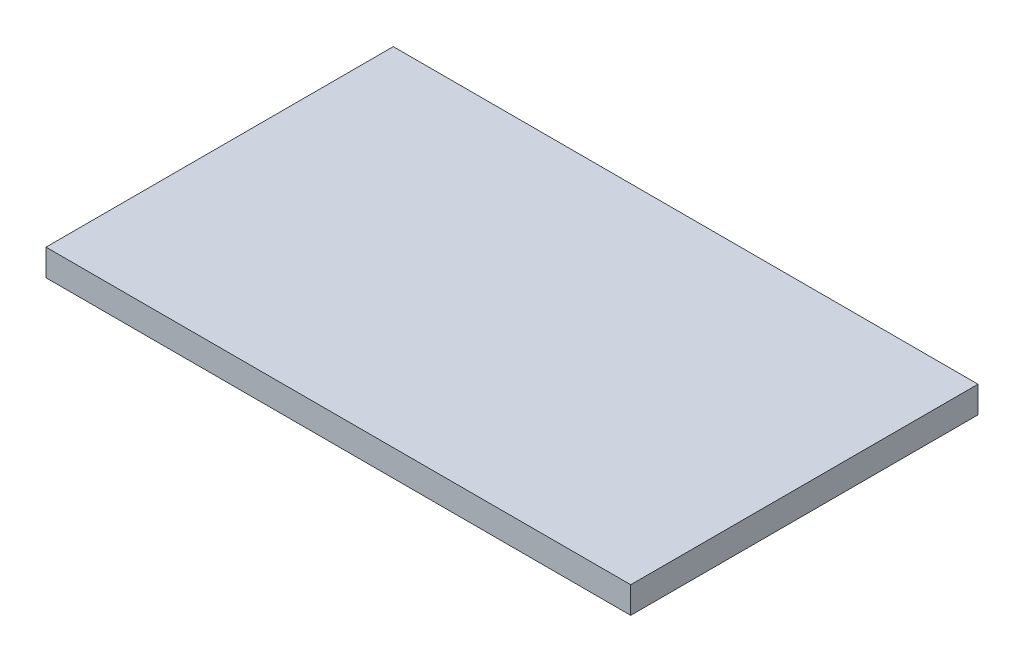
SolidWorks part; units mm, degrees
ref_plane "Front Plane" through (0, 0, 0) normal (0, 0, 1) x (1, 0, 0)
ref_plane "Top Plane" through (0, 0, 0) normal (0, 1, 0) x (1, 0, 0)
ref_plane "Right Plane" through (0, 0, 0) normal (1, 0, 0) x (0, 0, -1)
other "Configuration Table"
sketch "Sketch1" plane through (0, 0, 0) normal (0, 0, 1) x (1, 0, 0)
  line L1 (61.5, 1611) -> (1338.5, 1611)
  line L2 (61.5, 1611) -> (61.5, 1669)
  line L3 (61.5, 1669) -> (1338.5, 1669)
  line L4 (1338.5, 1611) -> (1338.5, 1669)
extrude "STORE_pu_tavan_1" add sketch "Sketch1" against normal blind 758.5 separate body
